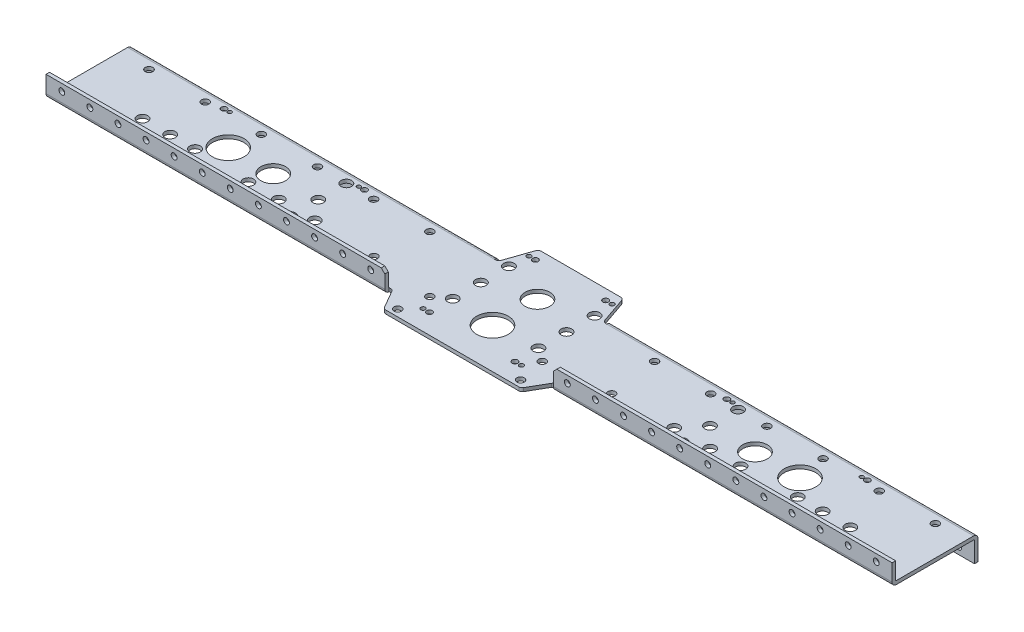
SolidWorks part; units mm, degrees
ref_plane "Front Plane" through (0, 0, 0) normal (0, 0, 1) x (1, 0, 0)
ref_plane "Top Plane" through (0, 0, 0) normal (0, 1, 0) x (1, 0, 0)
ref_plane "Right Plane" through (0, 0, 0) normal (1, 0, 0) x (0, 0, -1)
ref_plane "Plane1" through (0, 3.175, 0) normal (0, 1, 0) x (1, 0, 0)
sketch "Sketch1" plane through (0, 3.175, 0) normal (0, 1, 0) x (1, 0, 0)
  line L0 (457.2, 73.787) -> (457.2, -3.937)
  line L1 (457.2, -3.937) -> (812.8, -3.937)
  line L2 (812.8, -3.937) -> (812.8, 73.787)
  line L3 (812.8, 73.787) -> (457.2, 73.787)
extrude "Boss-Extrude1" add sketch "Sketch1" against normal blind 22.225
sketch "Sketch2" plane through (812.8, 0, 0) normal (1, 0, 0) x (0, 0, -1)
  line L0 (70.612, -19.05) -> (70.612, 0)
  line L1 (70.612, 0) -> (-3.937, 0)
  line L2 (-3.937, 0) -> (-3.937, -19.05)
  line L3 (-3.937, -19.05) -> (70.612, -19.05)
extrude "Cut-Extrude1" cut sketch "Sketch2" against normal through all
sketch "Sketch3" plane through (0, 0, 0) normal (0, -1, 0) x (1, 0, 0)
  line L0 (457.2, 0) -> (482.6, 0)
  line L1 (482.6, 0) -> (482.6, 3.937)
  line L2 (482.6, 3.937) -> (457.2, 3.937)
  line L3 (457.2, 3.937) -> (457.2, 0)
extrude "Cut-Extrude2" cut sketch "Sketch3" against normal through all
sketch "Sketch4" plane through (0, 3.175, 0) normal (0, 1, 0) x (-1, 0, 0)
  line L0 (-812.8, 3.937) -> (-482.6, 3.937)
  line L1 (-482.6, 3.937) -> (-482.6, 0.762)
  line L2 (-482.6, 0.762) -> (-812.8, 0.762)
  line L3 (-812.8, 0.762) -> (-812.8, 3.937)
extrude "Boss-Extrude2" add sketch "Sketch4" along normal blind 15.875
sketch "Sketch5" plane through (457.2, 0, 0) normal (-1, 0, 0) x (0, 0, 1)
  line L0 (0, 3.175) -> (0, 0)
  line L1 (0, 0) -> (-69.85, 0)
  line L2 (-69.85, 0) -> (-69.85, 3.175)
  line L3 (-69.85, 3.175) -> (0, 3.175)
extrude "Boss-Extrude3" add sketch "Sketch5" along normal blind 457.2
sketch "Sketch6" plane through (0, 0, 0) normal (0, 0, 1) x (1, 0, 0)
  line L0 (330.2, 3.175) -> (330.2, 0)
  line L1 (330.2, 0) -> (0, 0)
  line L2 (0, 0) -> (0, 3.175)
  line L3 (0, 3.175) -> (330.2, 3.175)
extrude "Boss-Extrude4" add sketch "Sketch6" along normal blind 3.937
sketch "Sketch7" plane through (0, 3.175, 0) normal (0, 1, 0) x (-1, 0, 0)
  line L0 (-330.2, 3.937) -> (0, 3.937)
  line L1 (0, 3.937) -> (0, 0.762)
  line L2 (0, 0.762) -> (-330.2, 0.762)
  line L3 (-330.2, 0.762) -> (-330.2, 3.937)
extrude "Boss-Extrude5" add sketch "Sketch7" along normal blind 15.875
sketch "Sketch8" plane through (0, 0, -69.85) normal (0, 0, -1) x (-1, 0, 0)
  line L0 (-355.6, 0) -> (-355.6, 3.175)
  line L1 (-355.6, 3.175) -> (0, 3.175)
  line L2 (0, 3.175) -> (0, 0)
  line L3 (0, 0) -> (-355.6, 0)
extrude "Boss-Extrude6" add sketch "Sketch8" along normal blind 3.937
sketch "Sketch9" plane through (0, 0, 0) normal (0, -1, 0) x (1, 0, 0)
  line L0 (0, -70.612) -> (355.6, -70.612)
  line L1 (355.6, -70.612) -> (355.6, -73.787)
  line L2 (355.6, -73.787) -> (0, -73.787)
  line L3 (0, -73.787) -> (0, -70.612)
extrude "Boss-Extrude7" add sketch "Sketch9" along normal blind 19.05
sketch "Sketch10" plane through (0, 0, 0) normal (0, 0, 1) x (1, 0, 0)
  line L0 (344.3735, 3.175) -> (468.4265, 3.175)
  line L1 (468.4265, 3.175) -> (468.4265, 0)
  line L2 (468.4265, 0) -> (344.3735, 0)
  line L3 (344.3735, 0) -> (344.3735, 3.175)
extrude "Boss-Extrude8" add sketch "Sketch10" along normal blind 19.05
sketch "Sketch11" plane through (0, 0, -69.85) normal (0, 0, -1) x (-1, 0, 0)
  line L0 (-444.5794, 3.175) -> (-368.2206, 3.175)
  line L1 (-368.2206, 3.175) -> (-368.2206, 0)
  line L2 (-368.2206, 0) -> (-444.5794, 0)
  line L3 (-444.5794, 0) -> (-444.5794, 3.175)
extrude "Boss-Extrude9" add sketch "Sketch11" along normal blind 27.432
draft "Draft1" type of draft neutral plane draft angle 30 faces to draft 2 face at (344.3735, 1.5875, 9.525) face at (468.4265, 1.5875, 9.525) neutral plane through (0, 0, 19.05) neutral plane normal (0, 0, 1) parameters "D1"=30
draft "Draft2" type of draft neutral plane draft angle 19 faces to draft 2 face at (368.2206, 1.5875, -83.566) face at (444.5794, 1.5875, -83.566) neutral plane through (0, 0, -97.282) neutral plane normal (0, 0, -1) parameters "D1"=19
hole_wizard "#6 Clearance Hole1" positions "Sketch13" profile "Sketch12" hole size "#6" standard "ANSI Inch"
sketch "Sketch13" plane through (0, 0, 0) normal (0, -1, 0) x (-1, 0, 0)
  point P0 (-450.8881, -1.0389)
  point P1 (-361.9119, -1.0389)
  point P2 (-368.808, 87.8535)
  point P3 (-443.992, 87.8535)
sketch "Sketch12" plane through (450.8881, 0, 1.0389) normal (1, 0, 0) x (0, 0, -1)
  line L0 (0, 0) -> (0, 19.05)
  line L1 (0, 19.05) -> (2.032, 19.05)
  line L2 (2.032, 19.05) -> (2.032, 0)
  line L5 (2.032, 0) -> (0, 0)
  line L11 (0, -6.35) -> (0, 107.95) construction
  dimension "Thru Hole Dia." = 4.064
  dimension "Thru Hole Depth" = 19.05
hole_wizard "Hole1" positions "Sketch15" profile "Sketch14" legacy
sketch "Sketch15" plane through (0, 0, 0) normal (0, -1, 0) x (-1, 0, 0)
  point P0 (-147.8292, 36.83)
  point P1 (-406.4, 17.272)
  point P2 (-664.9708, 36.83)
sketch "Sketch14" plane through (147.8292, 0, -36.83) normal (1, 0, 0) x (0, 0, -1)
  line L0 (0, 0) -> (0, 19.05)
  line L1 (0, 19.05) -> (14.2875, 19.05)
  line L2 (14.2875, 19.05) -> (14.2875, 0)
  line L3 (14.2875, 0) -> (0, 0)
  line L4 (0, 110) -> (0, -10) construction
  dimension "Diameter" = 28.575
  dimension "Depth" = 19.05
hole_wizard "7/8 (0.875) Diameter Hole1" positions "Sketch17" profile "Sketch16" hole size "7/8" standard "ANSI Inch"
sketch "Sketch17" plane through (0, 0, 0) normal (0, -1, 0) x (-1, 0, 0)
  point P0 (-188.5454, 36.83)
  point P1 (-406.4, 57.9628)
  point P2 (-624.2546, 36.83)
sketch "Sketch16" plane through (188.5454, 0, -36.83) normal (1, 0, 0) x (0, 0, -1)
  line L0 (0, 0) -> (0, 19.05)
  line L1 (0, 19.05) -> (11.1125, 19.05)
  line L2 (11.1125, 19.05) -> (11.1125, 0)
  line L5 (11.1125, 0) -> (0, 0)
  line L11 (0, -6.35) -> (0, 107.95) construction
  dimension "Thru Hole Dia." = 22.225
  dimension "Thru Hole Depth" = 19.05
hole_wizard "3/8 (0.375) Diameter Hole1" positions "Sketch19" profile "Sketch18" hole size "3/8" standard "ANSI Inch"
sketch "Sketch19" plane through (0, 0, 0) normal (0, -1, 0) x (-1, 0, 0)
  point P0 (-229.2616, 11.43)
  point P1 (-229.2616, 62.23)
  point P2 (-229.2616, 36.83)
  point P3 (-367.6757, 70.866)
  point P4 (-367.6757, 20.066)
  point P5 (-445.1243, 20.066)
  point P6 (-445.1243, 70.866)
  point P7 (-367.6757, 45.466)
  point P8 (-445.1243, 45.466)
  point P9 (-628.9477, 19.05)
  point P10 (-601.4385, 19.05)
  point P11 (-568.9249, 19.05)
  point P12 (-243.8751, 19.05)
  point P13 (-211.3615, 19.05)
  point P14 (-183.8523, 19.05)
  point P15 (-678.9442, 20.828)
  point P16 (-701.4504, 20.828)
  point P17 (-726.4609, 20.828)
  point P18 (-133.8558, 20.828)
  point P19 (-111.3496, 20.828)
  point P20 (-86.3391, 20.828)
  point P21 (-583.5384, 62.23)
  point P22 (-583.5384, 36.83)
  point P23 (-583.5384, 11.43)
sketch "Sketch18" plane through (229.2616, 0, -11.43) normal (1, 0, 0) x (0, 0, -1)
  line L0 (0, 0) -> (0, 19.05)
  line L1 (0, 19.05) -> (4.7625, 19.05)
  line L2 (4.7625, 19.05) -> (4.7625, 0)
  line L5 (4.7625, 0) -> (0, 0)
  line L11 (0, -6.35) -> (0, 107.95) construction
  dimension "Thru Hole Dia." = 9.525
  dimension "Thru Hole Depth" = 19.05
hole_wizard "#5 Clearance Hole1" positions "Sketch21" profile "Sketch20" hole size "#5" standard "ANSI Inch"
sketch "Sketch21" plane through (0, 0, 0) normal (0, -1, 0) x (-1, 0, 0)
  point P0 (-237.4404, 65.405)
  point P1 (-237.4404, 8.255)
  point P2 (-120.6004, 8.255)
  point P3 (-120.6004, 65.405)
  point P4 (-575.3596, 65.405)
  point P5 (-575.3596, 8.255)
  point P6 (-692.1996, 65.405)
  point P7 (-692.1996, 8.255)
sketch "Sketch20" plane through (237.4404, 0, -65.405) normal (1, 0, 0) x (0, 0, -1)
  line L0 (0, 0) -> (0, 19.05)
  line L1 (0, 19.05) -> (1.7859, 19.05)
  line L2 (1.7859, 19.05) -> (1.7859, 0)
  line L5 (1.7859, 0) -> (0, 0)
  line L11 (0, -6.35) -> (0, 107.95) construction
  dimension "Thru Hole Dia." = 3.5719
  dimension "Thru Hole Depth" = 19.05
hole_wizard "#7 (0.201) Diameter Hole1" positions "Sketch23" profile "Sketch22" hole size "#7" standard "ANSI Inch"
sketch "Sketch23" plane through (0, 0, 0) normal (0, -1, 0) x (-1, 0, 0)
  point P0 (-242.5204, 65.405)
  point P1 (-242.5204, 8.255)
  point P2 (-115.5204, 8.255)
  point P3 (-115.5204, 65.405)
  point P4 (-367.7539, -1.0389)
  point P5 (-445.0461, -1.0389)
  point P6 (-374.65, 87.8535)
  point P7 (-438.15, 87.8535)
  point P8 (-570.2796, 65.405)
  point P9 (-570.2796, 8.255)
  point P10 (-697.2796, 65.405)
  point P11 (-697.2796, 8.255)
sketch "Sketch22" plane through (242.5204, 0, -65.405) normal (1, 0, 0) x (0, 0, -1)
  line L0 (0, 0) -> (0, 19.05)
  line L1 (0, 19.05) -> (2.5527, 19.05)
  line L2 (2.5527, 19.05) -> (2.5527, 0)
  line L5 (2.5527, 0) -> (0, 0)
  line L11 (0, -6.35) -> (0, 107.95) construction
  dimension "Thru Hole Dia." = 5.1054
  dimension "Thru Hole Depth" = 19.05
hole_wizard "H (0.266) Diameter Hole1" positions "Sketch25" profile "Sketch24" hole size "H" standard "ANSI Inch"
sketch "Sketch25" plane through (0, 0, 0) normal (0, -1, 0) x (-1, 0, 0)
  point P0 (-508, 62.23)
  point P1 (-558.8, 11.43)
  point P2 (-558.8, 62.23)
  point P3 (-609.6, 11.43)
  point P4 (-457.2, 11.43)
  point P5 (-355.6, 11.43)
  point P6 (-304.8, 62.23)
  point P7 (-254, 62.23)
  point P8 (-152.4, 11.43)
  point P9 (-101.6, 62.23)
  point P10 (-101.6, 11.43)
  point P11 (-50.8, 62.23)
  point P12 (-254, 11.43)
  point P13 (-203.2, 62.23)
  point P14 (-203.2, 11.43)
  point P15 (-152.4, 62.23)
  point P16 (-711.2, 62.23)
  point P17 (-762, 11.43)
  point P18 (-762, 62.23)
  point P19 (-609.6, 62.23)
  point P20 (-660.4, 11.43)
  point P21 (-660.4, 62.23)
  point P22 (-711.2, 11.43)
  point P23 (-50.8, 11.43)
  point P24 (-461.9625, -12.8905)
  point P25 (-350.8375, -12.8905)
  point P26 (-513.9255, 17.5473)
  point P27 (-298.8745, 17.5473)
sketch "Sketch24" plane through (508, 0, -62.23) normal (1, 0, 0) x (0, 0, -1)
  line L0 (0, 0) -> (0, 19.05)
  line L1 (0, 19.05) -> (3.3782, 19.05)
  line L2 (3.3782, 19.05) -> (3.3782, 0)
  line L5 (3.3782, 0) -> (0, 0)
  line L11 (0, -6.35) -> (0, 107.95) construction
  dimension "Thru Hole Dia." = 6.7564
  dimension "Thru Hole Depth" = 19.05
hole_wizard "#10 Clearance Hole1" positions "Sketch27" profile "Sketch26" hole size "#10" standard "ANSI Inch"
sketch "Sketch27" plane through (0, 0, 3.937) normal (0, 0, 1) x (1, 0, 0)
  point P0 (495.3, 12.7)
  point P1 (520.7, 12.7)
  point P2 (546.1, 12.7)
  point P3 (571.5, 12.7)
  point P4 (596.9, 12.7)
  point P5 (622.3, 12.7)
  point P6 (647.7, 12.7)
  point P7 (673.1, 12.7)
  point P8 (698.5, 12.7)
  point P9 (723.9, 12.7)
  point P10 (749.3, 12.7)
  point P11 (774.7, 12.7)
  point P12 (800.1, 12.7)
  point P13 (317.5, 12.7)
  point P14 (292.1, 12.7)
  point P15 (266.7, 12.7)
  point P16 (241.3, 12.7)
  point P17 (215.9, 12.7)
  point P18 (190.5, 12.7)
  point P19 (165.1, 12.7)
  point P20 (139.7, 12.7)
  point P21 (114.3, 12.7)
  point P22 (88.9, 12.7)
  point P23 (63.5, 12.7)
  point P24 (12.7, 12.7)
  point P25 (38.1, 12.7)
sketch "Sketch26" plane through (495.3, 12.7, 3.937) normal (1, 0, 0) x (0, -1, 0)
  line L0 (0, 0) -> (0, 101.219)
  line L1 (0, 101.219) -> (2.667, 101.219)
  line L2 (2.667, 101.219) -> (2.667, 0)
  line L5 (2.667, 0) -> (0, 0)
  line L11 (0, -6.35) -> (0, 107.95) construction
  dimension "Thru Hole Dia." = 5.334
  dimension "Thru Hole Depth" = 101.219
hole_wizard "#10 Clearance Hole2" positions "Sketch29" profile "Sketch28" hole size "#10" standard "ANSI Inch"
sketch "Sketch29" plane through (0, 0, -70.612) normal (0, 0, 1) x (1, 0, 0)
  point P0 (469.9, -12.7)
  point P1 (495.3, -12.7)
  point P2 (520.7, -12.7)
  point P3 (546.1, -12.7)
  point P4 (571.5, -12.7)
  point P5 (596.9, -12.7)
  point P6 (622.3, -12.7)
  point P7 (647.7, -12.7)
  point P8 (673.1, -12.7)
  point P9 (698.5, -12.7)
  point P10 (723.9, -12.7)
  point P11 (749.3, -12.7)
  point P12 (774.7, -12.7)
  point P13 (800.1, -12.7)
  point P14 (342.9, -12.7)
  point P15 (317.5, -12.7)
  point P16 (292.1, -12.7)
  point P17 (266.7, -12.7)
  point P18 (241.3, -12.7)
  point P19 (215.9, -12.7)
  point P20 (190.5, -12.7)
  point P21 (165.1, -12.7)
  point P22 (139.7, -12.7)
  point P23 (114.3, -12.7)
  point P24 (88.9, -12.7)
  point P25 (63.5, -12.7)
  point P26 (38.1, -12.7)
  point P27 (12.7, -12.7)
sketch "Sketch28" plane through (469.9, -12.7, -70.612) normal (1, 0, 0) x (0, -1, 0)
  line L0 (0, 0) -> (0, 26.67)
  line L1 (0, 26.67) -> (2.667, 26.67)
  line L2 (2.667, 26.67) -> (2.667, 0)
  line L5 (2.667, 0) -> (0, 0)
  line L11 (0, -6.35) -> (0, 107.95) construction
  dimension "Thru Hole Dia." = 5.334
  dimension "Thru Hole Depth" = 26.67
chamfer "Chamfer1" distance 3.175 angle 45 8 edges at (0, -19.05, -72.1995) (0, 19.05, 2.3495) (330.2, 19.05, 2.3495) (812.8, 19.05, 2.3495) (355.6, -19.05, -72.1995) (482.6, 19.05, 2.3495) (812.8, -19.05, -72.1995) (457.2, -19.05, -72.1995)
fillet "Fillet1" radius 0.762 4 edges at (635, 0, -70.612) (165.1, 3.175, 0.762) (647.7, 3.175, 0.762) (177.8, 0, -70.612)
fillet "Fillet2" radius 3.175 8 edges at (344.3735, 1.5875, 19.05) (454.025, 1.5875, -69.85) (333.375, 1.5875, 0) (368.2206, 1.5875, -97.282) (358.775, 1.5875, -69.85) (468.4265, 1.5875, 19.05) (444.5794, 1.5875, -97.282) (479.425, 1.5875, 0)
fillet "Fillet3" radius 3.937 4 edges at (177.8, 3.175, -73.787) (165.1, 0, 3.937) (647.7, 0, 3.937) (635, 3.175, -73.787)
sketch "Sketch30" plane through (0, 0, 0) normal (0, -1, 0) x (-1, 0, 0)
  line L0 (-809.625, 73.787) -> (-460.375, 73.787) construction
  line L1 (-812.8, -3.937) -> (-788.9875, -3.937)
  line L2 (-812.8, -3.937) -> (-812.8, 73.787)
  line L3 (-812.8, 73.787) -> (-788.9875, 73.787)
  line L4 (-788.9875, -3.937) -> (-788.9875, 73.787)
  line L5 (-3.175, 73.787) -> (-352.425, 73.787) construction
  line L6 (0, -3.937) -> (-23.8125, -3.937)
  line L7 (0, -3.937) -> (0, 73.787)
  line L8 (0, 73.787) -> (-23.8125, 73.787)
  line L9 (-23.8125, -3.937) -> (-23.8125, 73.787)
  dimension "D1" = 765.175
extrude "Cut-Extrude3" cut sketch "Sketch30" against normal up to next and the other way up to next
